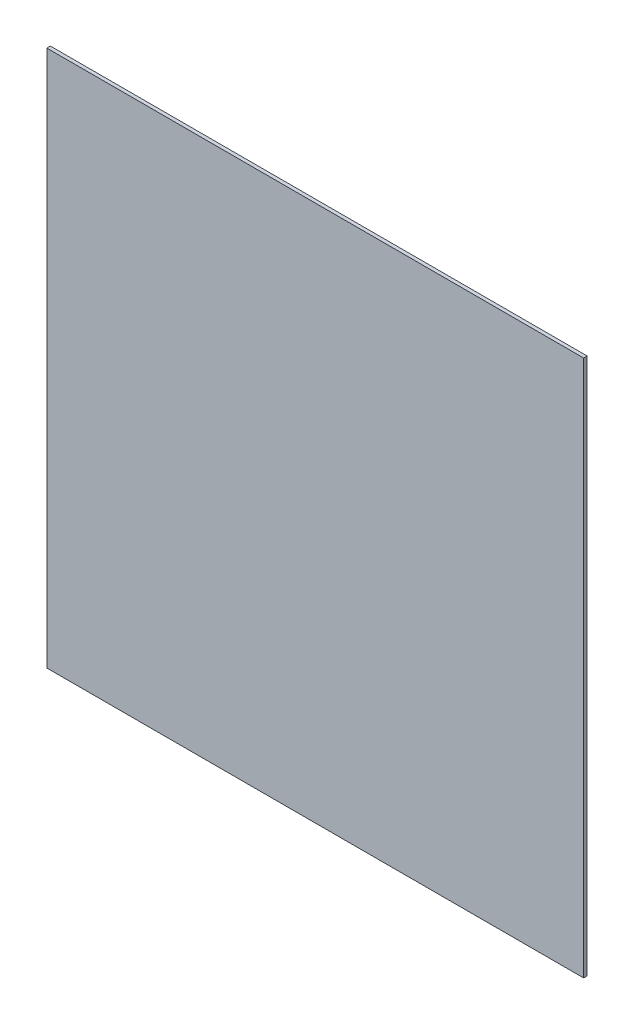
SolidWorks part; units mm, degrees
ref_plane "Спереди" through (0, 0, 0) normal (0, 0, 1) x (1, 0, 0)
ref_plane "Сверху" through (0, 0, 0) normal (0, 1, 0) x (1, 0, 0)
ref_plane "Справа" through (0, 0, 0) normal (1, 0, 0) x (0, 0, -1)
sketch "Эскиз1" plane through (0, 0, 0) normal (0, 0, 1) x (1, 0, 0)
  line L1 (-1501.9191, 1509.0509) -> (23.0809, 1509.0509)
  line L2 (-1501.9191, 1509.0509) -> (-1501.9191, -15.9491)
  line L3 (-1501.9191, -15.9491) -> (23.0809, -15.9491)
  line L4 (23.0809, 1509.0509) -> (23.0809, -15.9491)
  line L5 (-1501.9191, 1509.0509) -> (23.0809, -15.9491) construction
  line L6 (-1501.9191, -15.9491) -> (23.0809, 1509.0509) construction
  point P0 (-739.4191, 746.5509)
extrude "Бобышка-Вытянуть1" add sketch "Эскиз1" along normal blind 10
